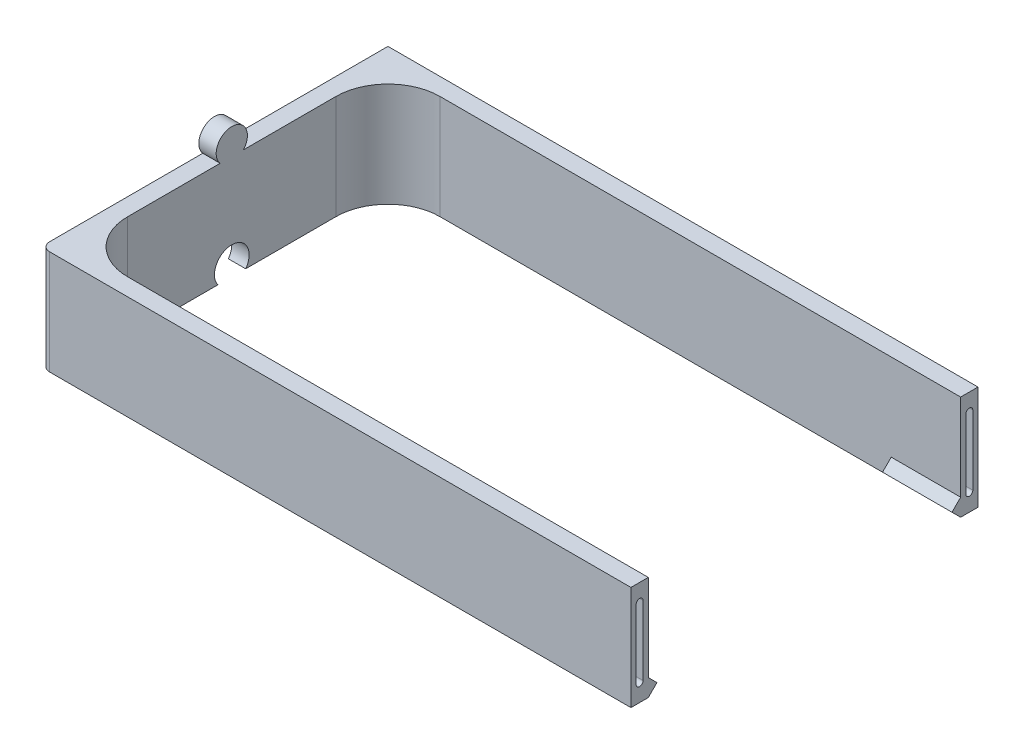
SolidWorks part; units mm, degrees
material "ABS"
ref_plane "Front Plane" through (0, 0, 0) normal (0, 0, 1) x (1, 0, 0)
ref_plane "Top Plane" through (0, 0, 0) normal (0, 1, 0) x (1, 0, 0)
ref_plane "Right Plane" through (0, 0, 0) normal (1, 0, 0) x (0, 0, -1)
sketch "Sketch1" plane through (0, 0, 0) normal (0, 1, 0) x (1, 0, 0)
  line L0 (2.5, 100) -> (0, 100)
  line L1 (2.5, 0) -> (305, 0)
  line L2 (0, 2.5) -> (0, 97.5)
  line L3 (2.5, 100) -> (305, 100)
  line L4 (320, 15) -> (320, 85)
  line L5 (20, 95) -> (300, 95)
  line L6 (5, 80) -> (5, 20)
  line L7 (20, 5) -> (300, 5)
  line L8 (315, 80) -> (315, 20)
  line L9 (0, 100) -> (0, 97.5)
  arc A1 (305, 0) -> (320, 15) centre (305, 15) ccw
  arc A2 (320, 85) -> (305, 100) centre (305, 85) ccw
  arc A3 (300, 5) -> (315, 20) centre (300, 20) ccw
  arc A4 (315, 80) -> (300, 95) centre (300, 80) ccw
  arc A5 (20, 5) -> (5, 20) centre (20, 20) cw
  arc A6 (5, 80) -> (20, 95) centre (20, 80) cw
  arc A7 (2.5, 0) -> (0, 2.5) centre (2.5, 2.5) cw
  point P25 (0, 0)
  dimension "D2" = 15
  dimension "D3" = 15
  dimension "D4" = 15
  dimension "D5" = 2.5
extrude "Boss-Extrude1" add sketch "Sketch1" along normal blind 30
sketch "Sketch2" plane through (0, 0, 0) normal (1, 0, 0) x (0, 0, -1)
  line L0 (0, 0) -> (50, 0)
  line L1 (100, 0) -> (2.5, 0) construction
  line L2 (50, 0) -> (50, 3)
  circle A0 centre (50, 3) radius 5
extrude "Cut-Extrude1" cut sketch "Sketch2" along normal blind 30
ref_plane "Plane1" through (160, 0, 0) normal (1, 0, 0) x (0, 0, -1)
sketch "Sketch3" plane through (160, 0, 0) normal (1, 0, 0) x (0, 0, -1)
  line L0 (5, 0) -> (5, 5)
  line L1 (5, 30) -> (5, 0) construction
  line L2 (5, 5) -> (7.5, 2.5)
  line L3 (7.5, 2.5) -> (5, 0)
  line L4 (95, 0) -> (95, 5)
  line L5 (95, 30) -> (95, 0) construction
  line L6 (95, 5) -> (92.5, 2.5)
  line L7 (92.5, 2.5) -> (95, 0)
extrude "Boss-Extrude2" add sketch "Sketch3" along normal blind 10 and the other way blind 10
sketch "Sketch4" plane through (0, 0, 0) normal (0, 1, 0) x (1, 0, 0)
  line L1 (2.5, 0) -> (305, 0) construction
  line L2 (170, 0) -> (170, 100)
  line L3 (305, 100) -> (0, 100) construction
  line L4 (170, 100) -> (329.061, 100)
  line L5 (329.061, 100) -> (329.061, 0)
  line L6 (329.061, 0) -> (170, 0)
extrude "Cut-Extrude2" cut sketch "Sketch4" along normal blind 55
sketch "Sketch5" plane through (160, 0, 0) normal (1, 0, 0) x (0, 0, -1)
  line L0 (2.5, 30) -> (2.5, 0)
  line L1 (5, 30) -> (0, 30) construction
  line L2 (5, 0) -> (0, 0) construction
  line L3 (2.5, 5) -> (2.5, 25) construction
  line L4 (1.5, 5) -> (1.5, 25)
  line L5 (3.5, 5) -> (3.5, 25)
  line L6 (97.5, 30) -> (97.5, 0)
  line L7 (100, 30) -> (95, 30) construction
  line L8 (100, 0) -> (95, 0) construction
  line L9 (97.5, 5) -> (97.5, 25) construction
  line L10 (96.5, 5) -> (96.5, 25)
  line L11 (98.5, 5) -> (98.5, 25)
  arc A0 (1.5, 5) -> (3.5, 5) centre (2.5, 5) ccw
  arc A1 (3.5, 25) -> (1.5, 25) centre (2.5, 25) ccw
  arc A2 (96.5, 5) -> (98.5, 5) centre (97.5, 5) ccw
  arc A3 (98.5, 25) -> (96.5, 25) centre (97.5, 25) ccw
  point P8 (2.5, 15)
  point P21 (97.5, 15)
extrude "Cut-Extrude3" cut sketch "Sketch5" against normal blind 5 and the other way blind 10 contours L5 A1 L0 A0 | L0 A1 L4 A0 | L11 A3 L6 A2 | L6 A3 L10 A2
sketch "Sketch6" plane through (0, 0, 0) normal (1, 0, 0) x (0, 0, -1)
  line L0 (50, 30) -> (50, 33)
  line L1 (80, 30) -> (20, 30) construction
  circle A0 centre (50, 33) radius 4.5
extrude "Boss-Extrude3" add sketch "Sketch6" along normal blind 5
